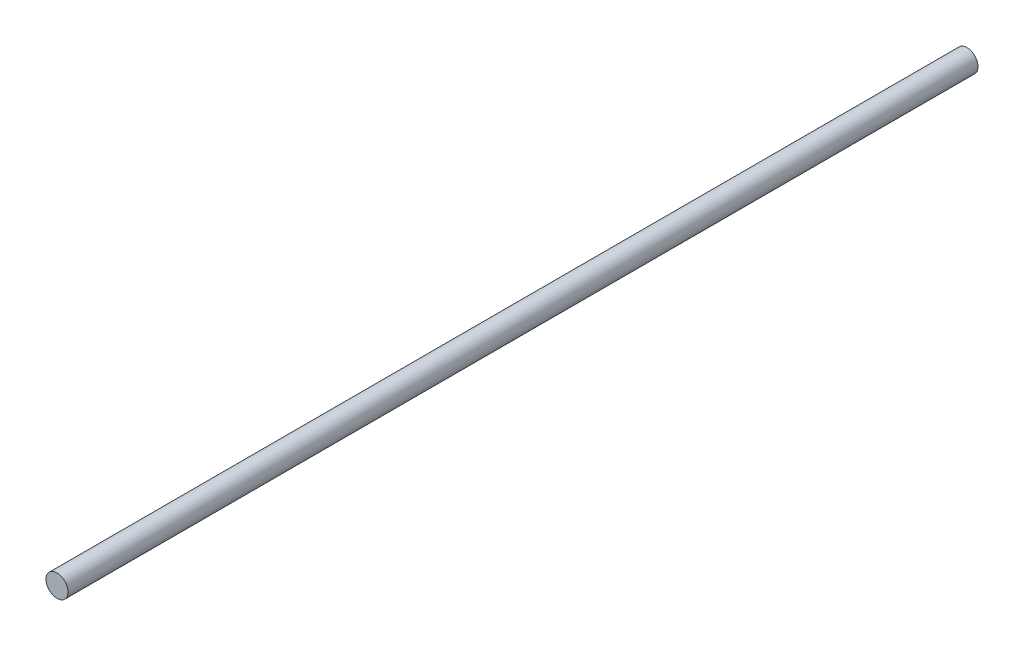
SolidWorks part; units mm, degrees
ref_plane "Front Plane" through (0, 0, 0) normal (0, 0, 1) x (1, 0, 0)
ref_plane "Top Plane" through (0, 0, 0) normal (0, 1, 0) x (1, 0, 0)
ref_plane "Right Plane" through (0, 0, 0) normal (1, 0, 0) x (0, 0, -1)
sketch "Sketch1" plane through (0, 0, 0) normal (0, 0, 1) x (1, 0, 0)
  circle A0 centre (0, 0) radius 4
  point P3 (0, 0)
  dimension "D1" = 8
extrude "Boss-Extrude1" add sketch "Sketch1" against normal blind 330
